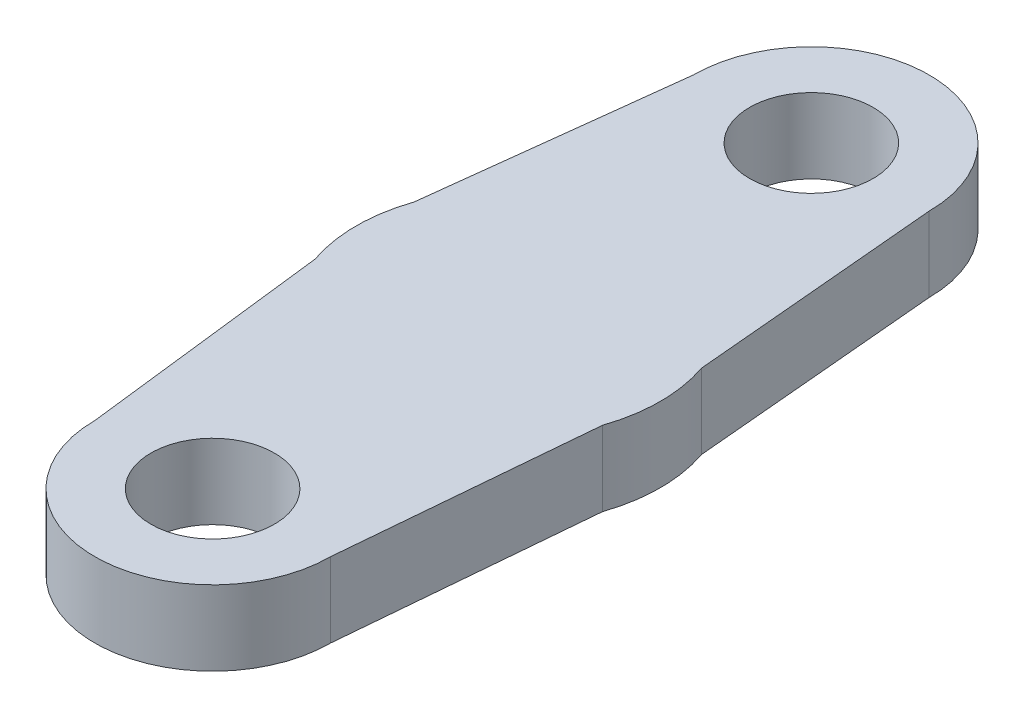
SolidWorks part; units mm, degrees
ref_plane "Alzado" through (0, 0, 0) normal (0, 0, 1) x (1, 0, 0)
ref_plane "Planta" through (0, 0, 0) normal (0, 1, 0) x (1, 0, 0)
ref_plane "Vista lateral" through (0, 0, 0) normal (1, 0, 0) x (0, 0, -1)
sketch "Croquis1" plane through (0, 0, 0) normal (0, 1, 0) x (1, 0, 0)
  line L0 (-3.05, 8) -> (-3.8431, 1.321)
  line L1 (-3.8431, -1.321) -> (-3.05, -8)
  line L2 (3.25, 8) -> (3.8431, 1.321)
  line L3 (3.8431, -1.321) -> (3.25, -8)
  arc A0 (3.8431, -1.321) -> (3.8431, 1.321) centre (0, 0) ccw
  circle A1 centre (0.1, 8) radius 1.65
  circle A2 centre (0.1, -8) radius 1.65
  arc A3 (3.25, 8) -> (-3.05, 8) centre (0.1, 8) ccw
  arc A4 (-3.05, -8) -> (3.25, -8) centre (0.1, -8) ccw
  circle A5 centre (0.1, -8) radius 3.15 construction
  circle A7 centre (0.1, 8) radius 3.15 construction
  arc A8 (-3.8431, 1.321) -> (-3.8431, -1.321) centre (0, 0) ccw
  dimension "D3" = 3.3
  dimension "D5" = 3.3
  dimension "D4" = 16
  dimension "D1" = 1.5
  dimension "D2" = 1.5
extrude "Saliente-Extruir1" add sketch "Croquis1" along normal blind 2
